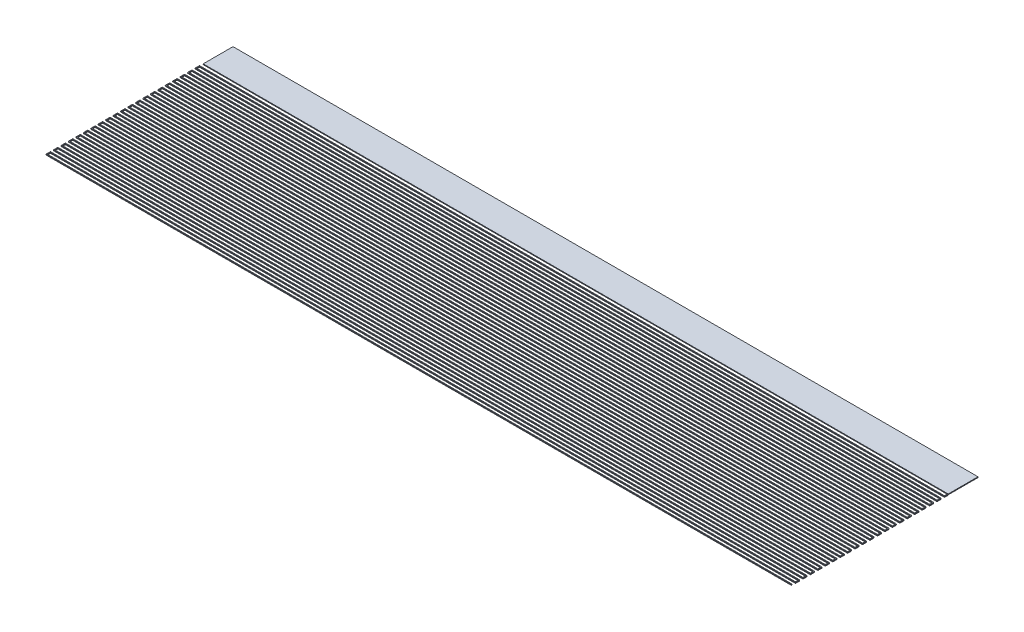
SolidWorks part; units mm, degrees
ref_plane "Front Plane" through (0, 0, 0) normal (0, 0, 1) x (1, 0, 0)
ref_plane "Top Plane" through (0, 0, 0) normal (0, 1, 0) x (1, 0, 0)
ref_plane "Right Plane" through (0, 0, 0) normal (1, 0, 0) x (0, 0, -1)
sketch "Sketch1" plane through (0, 0, 0) normal (0, 1, 0) x (1, 0, 0)
  line L1 (0, 0) -> (200, 0)
  line L2 (0, 0) -> (0, 8)
  line L3 (0, 8) -> (200, 8)
  line L4 (200, 0) -> (200, 8)
  dimension "D1" = 200
  dimension "D2" = 8
extrude "Boss-Extrude1" add sketch "Sketch1" along normal blind 0.2
sketch "Sketch2" plane through (0, 0, 0) normal (0, 1, 0) x (1, 0, 0)
  line L0 (200, 0) -> (200, -1)
  line L1 (200, -1) -> (0, -1)
  line L2 (0, -1) -> (0, -2)
  line L3 (0, -2) -> (200, -2)
  dimension "D1" = 1
  dimension "D2" = 1
extrude "Extrude-Thin1" add sketch "Sketch2" along normal blind 0.2 thin contours L0 L1 L2 L3 thin type mid plane wall 0.2
pattern_linear "LPattern1" count 21 spacing 2 along (0, 0, 1) of "Extrude-Thin1"
